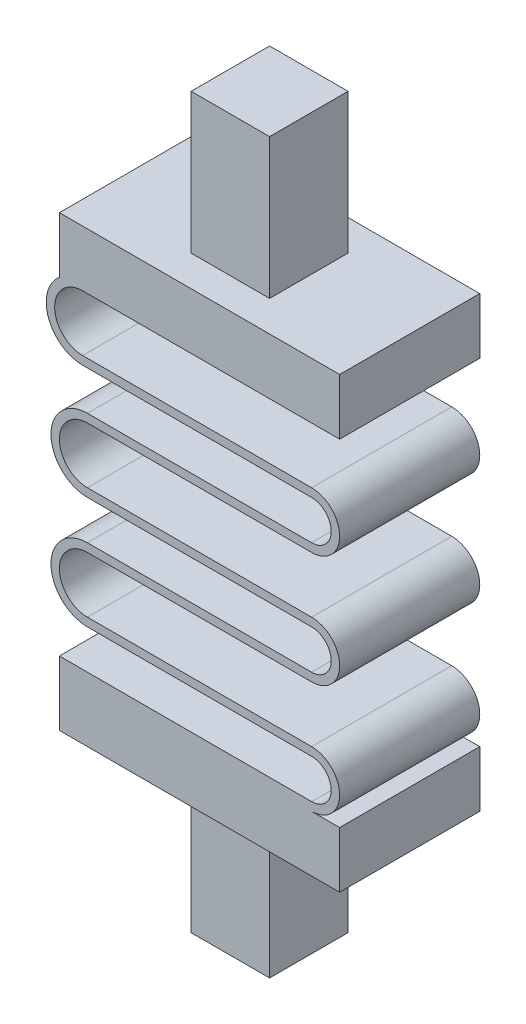
SolidWorks part; units mm, degrees
ref_plane "Front Plane" through (0, 0, 0) normal (0, 0, 1) x (1, 0, 0)
ref_plane "Top Plane" through (0, 0, 0) normal (0, 1, 0) x (1, 0, 0)
ref_plane "Right Plane" through (0, 0, 0) normal (1, 0, 0) x (0, 0, -1)
sketch "Sketch2" plane through (0, 0, 0) normal (0, 0, 1) x (1, 0, 0)
  line L0 (-4.1693, 2.5732) -> (4, 2.5732)
  line L1 (-5, -7.4268) -> (5, -7.4268)
  line L2 (-5, -7.4268) -> (-5, -9.4268)
  line L3 (-5, -9.4268) -> (5, -9.4268)
  line L4 (5, -7.4268) -> (5, -9.4268)
  line L5 (-5, 6.5732) -> (5, 6.5732)
  line L6 (-5, 6.5732) -> (-5, 4.5732)
  line L7 (-5, 4.5732) -> (5, 4.5732)
  line L8 (5, 6.5732) -> (5, 4.5732)
  line L10 (-4, 0.5732) -> (4, 0.5732)
  line L12 (-4, -1.4268) -> (4, -1.4268)
  line L14 (-4, -3.4268) -> (4, -3.4268)
  line L16 (-4, 0.5732) -> (4, 0.5732)
  line L18 (-4, -1.4268) -> (4, -1.4268)
  line L20 (-4, -5.4268) -> (4, -5.4268)
  line L22 (-5, -7.4268) -> (5, -7.4268)
  line L24 (-4, -3.4268) -> (4, -3.4268)
  line L26 (-4, -5.4268) -> (4, -5.4268)
  line L28 (-5, 4.5732) -> (5, 4.5732)
  line L30 (-4.1693, 2.5732) -> (4, 2.5732)
  line L31 (-4.1693, 2.2732) -> (4, 2.2732)
  line L32 (-4, 0.8732) -> (4, 0.8732)
  line L33 (-4, -1.7268) -> (4, -1.7268)
  line L34 (-4, -3.1268) -> (4, -3.1268)
  line L35 (-4, -5.7268) -> (4, -5.7268)
  line L36 (4, -7.1268) -> (-5, -7.1268)
  line L37 (-5, -7.1268) -> (-5, -7.4268)
  arc A0 (-4.1693, 4.5732) -> (-4.1693, 2.5732) centre (-4.1693, 3.5732) ccw
  arc A1 (4, 0.5732) -> (4, 2.5732) centre (4, 1.5732) ccw
  arc A3 (-4, 0.5732) -> (-4, -1.4268) centre (-4, -0.4268) ccw
  arc A4 (4, -7.4268) -> (4, -5.4268) centre (4, -6.4268) ccw
  arc A5 (-4, -3.4268) -> (-4, -5.4268) centre (-4, -4.4268) ccw
  arc A6 (4, -3.4268) -> (4, -1.4268) centre (4, -2.4268) ccw
  arc A7 (-5, 4.5732) -> (-4.1693, 2.2732) centre (-4.1693, 3.5732) ccw
  arc A8 (4, 0.8732) -> (4, 2.2732) centre (4, 1.5732) ccw
  arc A9 (-4, 0.8732) -> (-4, -1.7268) centre (-4, -0.4268) ccw
  arc A10 (4, -3.1268) -> (4, -1.7268) centre (4, -2.4268) ccw
  arc A11 (-4, -3.1268) -> (-4, -5.7268) centre (-4, -4.4268) ccw
  arc A12 (4, -7.1268) -> (4, -5.7268) centre (4, -6.4268) ccw
  arc A13 (-4.1693, 4.8732) -> (-4.1693, 2.2732) centre (-4.1693, 3.5732) ccw construction
  point P8 (0, -7.4268)
  point P10 (0, 4.5732)
  dimension "D4" = 0.3
  dimension "D3" = 2
  dimension "D1" = 10
  dimension "D2" = 2
extrude "Boss-Extrude1" add sketch "Sketch2" along normal blind 5 contours L8 L5 L6 L7 L28 | A12 L36 L37 L1 A4 L20 A5 L14 A6 L12 A3 L10 A1 L0 A0 L7 L6 A7 L31 A8 L32 A9 L33 A10 L34 A11 L35 | L4 L22 L1 L2 L3
sketch "Sketch3" plane through (0, 6.5732, 0) normal (0, 1, 0) x (1, 0, 0)
  line L0 (0, 0) -> (0, -5) construction
  line L1 (-1.4, -3.9) -> (1.4, -3.9)
  line L2 (-1.4, -3.9) -> (-1.4, -1.1)
  line L3 (-1.4, -1.1) -> (1.4, -1.1)
  line L4 (1.4, -3.9) -> (1.4, -1.1)
  line L5 (-1.4, -3.9) -> (1.4, -1.1) construction
  line L6 (-1.4, -1.1) -> (1.4, -3.9) construction
  line L7 (-5, 0) -> (5, 0) construction
  line L8 (-5, -5) -> (5, -5) construction
  point P0 (0, -2.5)
  point P12 (0, -2.5)
  dimension "D1" = 2.8
  dimension "D2" = 2.8
extrude "Boss-Extrude2" add sketch "Sketch3" along normal blind 5
sketch "Sketch4" plane through (0, -9.4268, 0) normal (0, -1, 0) x (1, 0, 0)
  line L0 (0, 5) -> (0, 0) construction
  line L1 (-5, 5) -> (5, 5) construction
  line L3 (1.4, 1.1) -> (-1.4, 1.1)
  line L4 (1.4, 1.1) -> (1.4, 3.9)
  line L5 (1.4, 3.9) -> (-1.4, 3.9)
  line L6 (-1.4, 1.1) -> (-1.4, 3.9)
  line L7 (1.4, 1.1) -> (-1.4, 3.9) construction
  line L8 (1.4, 3.9) -> (-1.4, 1.1) construction
  point P5 (0, 2.5)
  dimension "D1" = 2.8
  dimension "D2" = 2.8
extrude "Boss-Extrude3" add sketch "Sketch4" along normal blind 5
